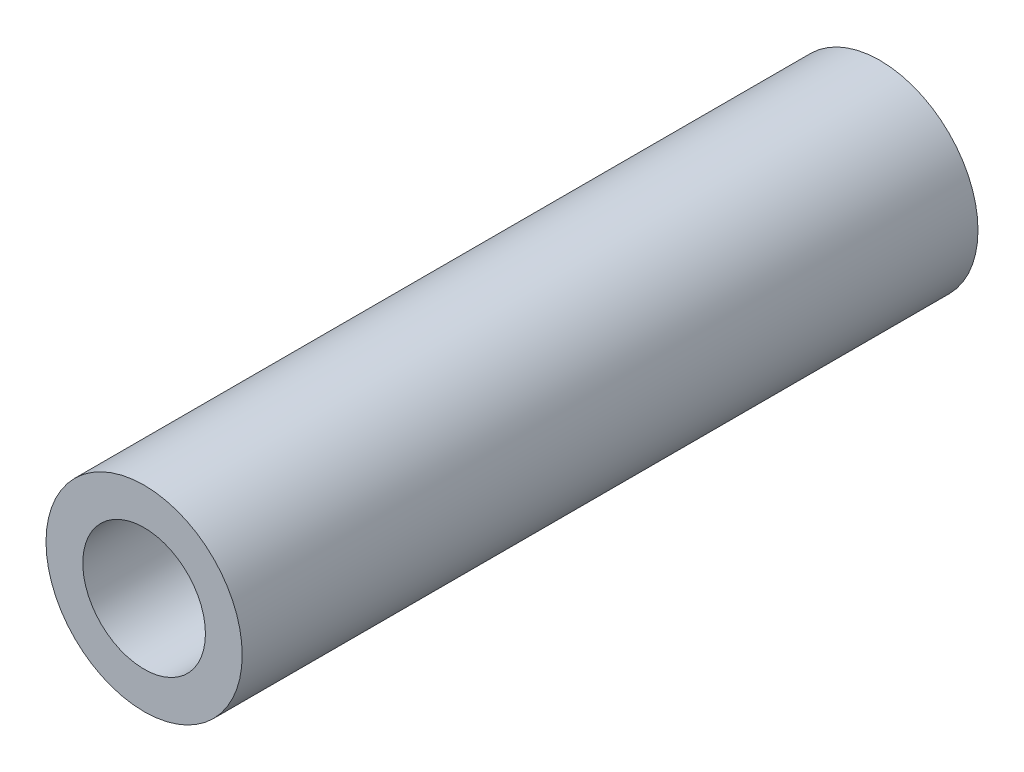
SolidWorks part; units mm, degrees
material "PVC 0.007 Plasticized"
ref_plane "Front Plane" through (0, 0, 0) normal (0, 0, 1) x (1, 0, 0)
ref_plane "Top Plane" through (0, 0, 0) normal (0, 1, 0) x (1, 0, 0)
ref_plane "Right Plane" through (0, 0, 0) normal (1, 0, 0) x (0, 0, -1)
sketch "Sketch1" plane through (0, 0, 0) normal (0, 0, 1) x (1, 0, 0)
  circle A0 centre (0, 0) radius 2.5
  circle A1 centre (0, 0) radius 4
  dimension "D1" = 5
  dimension "D2" = 8
extrude "Boss-Extrude1" add sketch "Sketch1" along normal blind 30
